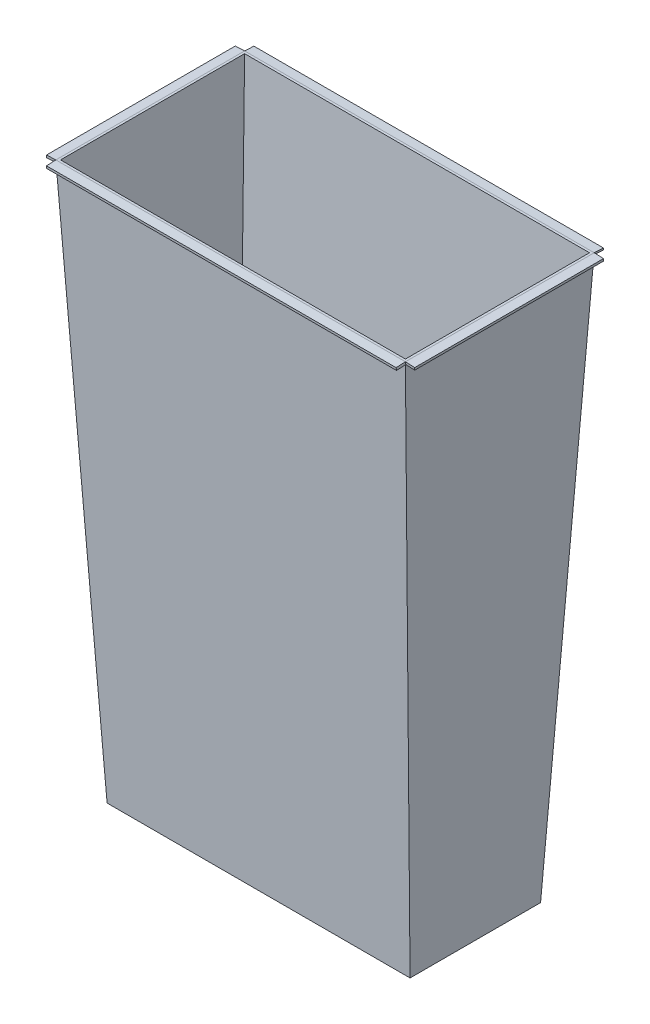
SolidWorks part; units mm, degrees
ref_plane "Front Plane" through (0, 0, 0) normal (0, 0, 1) x (1, 0, 0)
ref_plane "Top Plane" through (0, 0, 0) normal (0, 1, 0) x (1, 0, 0)
ref_plane "Right Plane" through (0, 0, 0) normal (1, 0, 0) x (0, 0, -1)
sketch "Sketch1" plane through (0, 0, 0) normal (0, 1, 0) x (1, 0, 0)
  line L0 (0, 0) -> (0, 282.575)
  line L1 (0, 282.575) -> (501.65, 282.575)
  line L2 (501.65, 282.575) -> (501.65, 0)
  line L3 (501.65, 0) -> (0, 0)
  line L4 (12.7, 269.875) -> (12.7, 12.7)
  line L5 (12.7, 12.7) -> (488.95, 12.7)
  line L6 (488.95, 12.7) -> (488.95, 269.875)
  line L7 (488.95, 269.875) -> (12.7, 269.875)
  dimension "D1" = 282.575
  dimension "D2" = 501.65
  dimension "D3" = 12.7
  dimension "D4" = 12.7
  dimension "D5" = 12.7
  dimension "D6" = 12.7
ref_plane "Plane1" through (0, -762, 0) normal (0, 1, 0) x (1, 0, 0)
sketch "Sketch6" plane through (0, -762, 0) normal (0, 1, 0) x (1, 0, 0)
  line L0 (0, 0) -> (450.85, 0) construction
  line L1 (44.45, 50.8) -> (457.2, 50.8)
  line L2 (44.45, 228.6) -> (457.2, 228.6)
  line L3 (0, 228.6) -> (0, 0) construction
  line L4 (44.45, 228.6) -> (44.45, 50.8)
  line L5 (457.2, 228.6) -> (457.2, 50.8)
  dimension "D1" = 44.45
  dimension "D2" = 177.8
  dimension "D3" = 412.75
  dimension "D5" = 50.8
loft "Loft1" add profiles "Sketch1", "Sketch6"
shell "Shell2" thickness 3.175
sketch "Sketch7" plane through (12.678, 0.5282, 0) normal (-0.9991, -0.0416, 0) x (0, 0, 1)
  line L0 (-269.875, -0.5287) -> (-12.7, -0.5287)
  line L1 (-12.7, -0.5287) -> (-12.7, -3.7037)
  line L2 (-12.7, -3.7037) -> (-269.7032, -3.7037)
  line L3 (-269.875, -0.5287) -> (-228.6, -763.1899) construction
  line L4 (-269.875, -0.5287) -> (-269.7032, -3.7037)
  dimension "D1" = 3.175
extrude "Boss-Extrude3" add sketch "Sketch7" along normal blind 12.7
sketch "Sketch8" plane through (0, -14.5755, -269.0855) normal (0, -0.0541, -0.9985) x (-1, 0, 0)
  line L0 (-12.7, 14.5968) -> (-488.95, 14.5968)
  line L1 (-488.95, 14.5968) -> (-488.8465, 12.1087)
  line L2 (-488.95, 14.5968) -> (-457.2, -748.5202) construction
  line L3 (-488.8465, 12.1087) -> (-12.8035, 12.1087)
  line L4 (-12.8322, 11.4199) -> (-44.45, -748.5202) construction
  line L5 (0, 15.2837) -> (-501.65, 15.2837) construction
  arc A0 (-12.8035, 12.1087) -> (-12.7, 14.5968) centre (17.1491, 12.1087) cw
  dimension "D1" = 3.175
extrude "Boss-Extrude4" add sketch "Sketch8" along normal blind 12.7
sketch "Sketch9" plane through (488.1026, -20.3376, 0) normal (0.9991, -0.0416, 0) x (0, 0, -1)
  line L0 (12.7, 20.3553) -> (269.875, 20.3553)
  line L1 (269.875, 20.3553) -> (269.7032, 17.1803)
  line L2 (269.7404, 17.8687) -> (228.6, -742.3059) construction
  line L3 (269.7032, 17.1803) -> (12.8586, 17.1803)
  line L4 (12.7, 20.3553) -> (50.8, -742.3059) construction
  line L5 (12.8586, 17.1803) -> (12.7, 20.3553)
  dimension "D1" = 3.175
extrude "Boss-Extrude5" add sketch "Sketch9" along normal blind 12.7
sketch "Sketch10" plane through (0, 0.6334, -12.6683) normal (0, -0.0499, 0.9988) x (1, 0, 0)
  line L0 (12.7, -0.6342) -> (488.95, -0.6342)
  line L1 (488.95, -0.6342) -> (489.3544, -3.8092)
  line L2 (488.8178, -16.6366) -> (457.2, -772.465) construction
  line L3 (489.3544, -3.8092) -> (12.8321, -3.8092)
  line L4 (12.8322, -3.8104) -> (44.45, -763.5861) construction
  line L5 (12.8321, -3.8092) -> (12.7, -0.6342)
  dimension "D1" = 3.175
extrude "Boss-Extrude6" add sketch "Sketch10" along normal blind 12.7
sketch "Sketch11" plane through (0.8474, 20.3376, 0) normal (0.0416, 0.9991, 0) x (0.9991, -0.0416, 0)
  line L0 (493.2811, 246.2875) -> (493.2811, 36.2875) construction
  line L1 (501.2151, 282.575) -> (501.2151, 0) construction
  line L2 (485.3511, 15.879) -> (485.3511, 266.6953) construction
  line L3 (508.1746, 208.5975) -> (508.1746, 73.9775) construction
  line L4 (493.2811, 141.2875) -> (508.1746, 141.2875) construction
  line L5 (493.2811, 229.2875) -> (493.2811, 224.7875) construction
  circle A0 centre (493.2811, 19.2875) radius 2.1
  circle A1 centre (493.2811, 53.2875) radius 2.1
  circle A2 centre (493.2811, 263.2875) radius 2.1
  circle A3 centre (493.2811, 229.2875) radius 2.1
  point P2 (493.2811, 141.2875)
  point P5 (501.2151, 141.2875)
  point P20 (508.1746, 141.2875)
  dimension "D1" = 4.2
  dimension "D5" = 4.2
  dimension "D2" = 7.93
  dimension "D3" = 17
  dimension "D4" = 210
  dimension "D6" = 17
  dimension "D7" = 134.62
  dimension "D8" = 4.5
